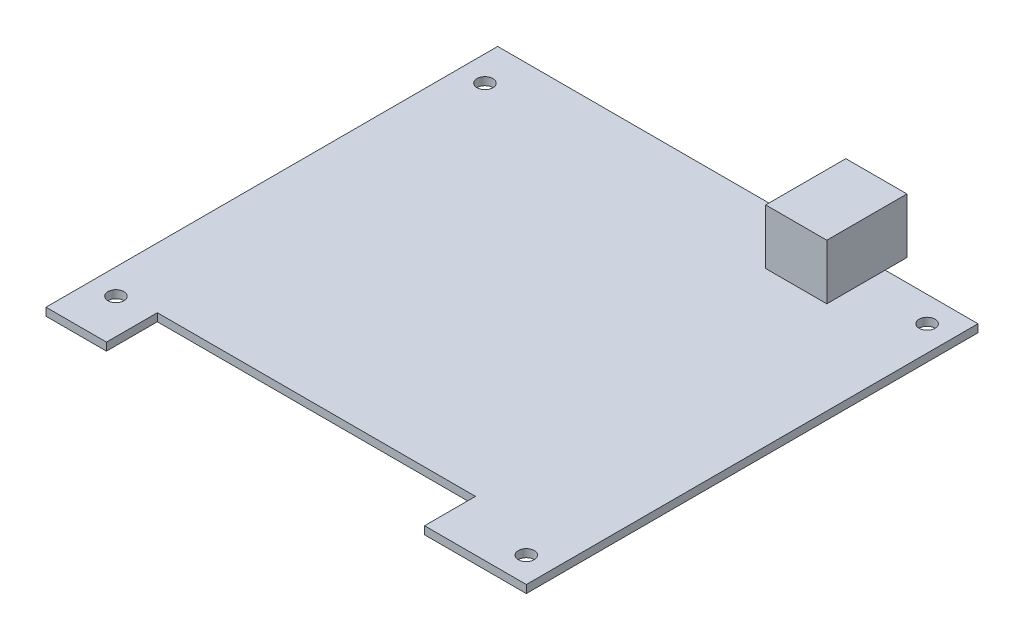
SolidWorks part; units mm, degrees
material "E-Glass Fiber"
ref_plane "Front Plane" through (0, 0, 0) normal (0, 0, 1) x (1, 0, 0)
ref_plane "Top Plane" through (0, 0, 0) normal (0, 1, 0) x (1, 0, 0)
ref_plane "Right Plane" through (0, 0, 0) normal (1, 0, 0) x (0, 0, -1)
sketch "Sketch1" plane through (0, 0, 0) normal (0, 1, 0) x (1, 0, 0)
  line L0 (-35.875, -45.085) -> (-47.945, -45.085)
  line L1 (47.945, -45.085) -> (27.625, -45.085)
  line L2 (47.945, -45.085) -> (47.945, 45.085)
  line L3 (47.945, 45.085) -> (-47.945, 45.085)
  line L4 (-47.945, -45.085) -> (-47.945, 45.085)
  line L5 (47.945, -45.085) -> (-47.945, 45.085) construction
  line L6 (47.945, 45.085) -> (-47.945, -45.085) construction
  line L8 (-35.875, -45.085) -> (-35.875, -34.925)
  line L9 (-35.875, -34.925) -> (27.625, -34.925)
  line L10 (27.625, -45.085) -> (27.625, -34.925)
  point P0 (0, 0)
  dimension "D1" = 90.17
  dimension "D2" = 95.89
  dimension "D3" = 20.32
  dimension "D4" = 10.16
  dimension "D5" = 83.82
extrude "Boss-Extrude1" add sketch "Sketch1" along normal blind 1.57
sketch "Sketch2" plane through (0, 1.57, 0) normal (0, 1, 0) x (1, 0, 0)
  line L0 (27.625, -45.085) -> (47.945, -45.085) construction
  line L1 (47.945, -45.085) -> (47.945, 45.085) construction
  circle A0 centre (42.865, -40.005) radius 1.59
  circle A1 centre (-42.865, -36.195) radius 1.59
  circle A2 centre (-42.865, 37.465) radius 1.59
  circle A3 centre (42.865, 40.005) radius 1.59
  dimension "D3" = 3.18
  dimension "D6" = 3.18
  dimension "D9" = 3.18
  dimension "D12" = 3.18
  dimension "D1" = 5.08
  dimension "D2" = 5.08
  dimension "D4" = 8.89
  dimension "D5" = 90.81
  dimension "D7" = 5.08
  dimension "D8" = 85.09
  dimension "D10" = 90.81
  dimension "D11" = 82.55
extrude "Cut-Extrude1" cut sketch "Sketch2" against normal through all
sketch "Sketch3" plane through (0, 1.57, 0) normal (0, 1, 0) x (1, 0, 0)
  line L0 (47.945, -45.085) -> (47.945, 45.085) construction
  line L1 (17.211, 49.435) -> (29.411, 49.435)
  line L2 (17.211, 49.435) -> (17.211, 33.435)
  line L3 (17.211, 33.435) -> (29.411, 33.435)
  line L4 (29.411, 49.435) -> (29.411, 33.435)
  line L5 (47.945, 45.085) -> (-47.945, 45.085) construction
  dimension "D1" = 16
  dimension "D2" = 12.2
  dimension "D3" = 30.734
  dimension "D4" = 4.35
extrude "Boss-Extrude2" add sketch "Sketch3" along normal blind 11 separate body
